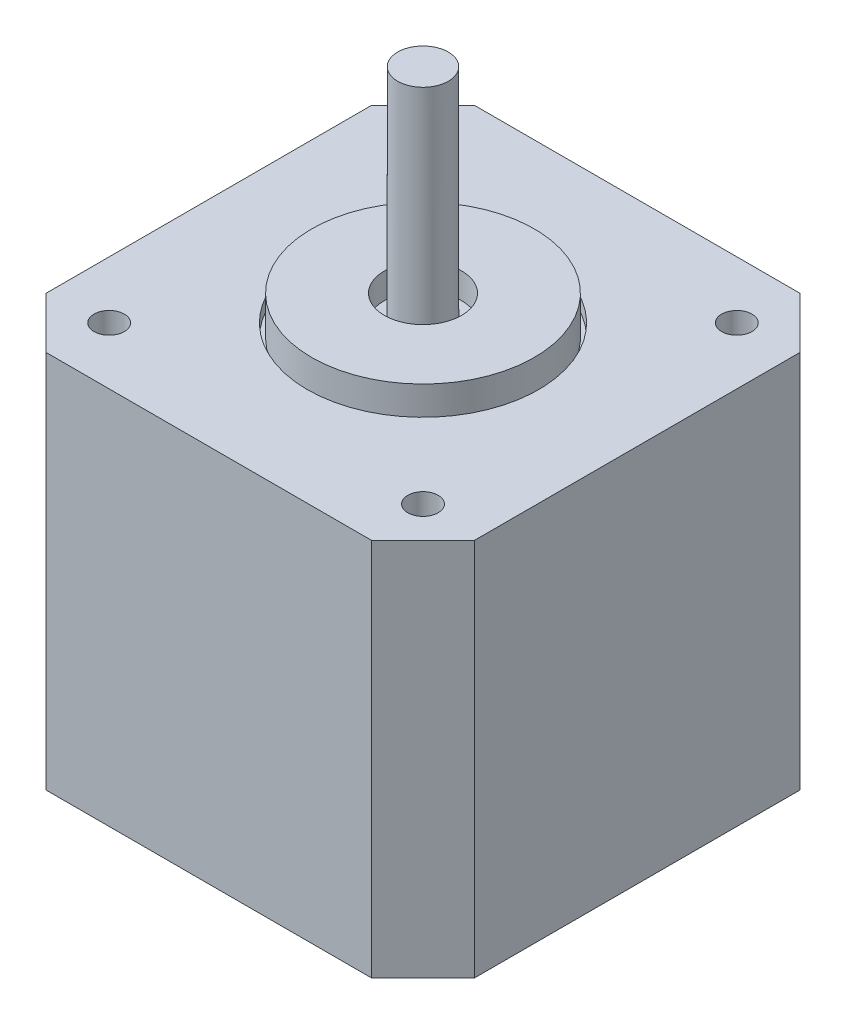
SolidWorks part; units mm, degrees
ref_plane "Front Plane" through (0, 0, 0) normal (0, 0, 1) x (1, 0, 0)
ref_plane "Top Plane" through (0, 0, 0) normal (0, 1, 0) x (1, 0, 0)
ref_plane "Right Plane" through (0, 0, 0) normal (1, 0, 0) x (0, 0, -1)
sketch "Sketch1" plane through (0, 0, 0) normal (0, 1, 0) x (1, 0, 0)
  line L1 (-21.15, -21.15) -> (21.15, -21.15)
  line L2 (-21.15, -21.15) -> (-21.15, 21.15)
  line L3 (-21.15, 21.15) -> (21.15, 21.15)
  line L4 (21.15, -21.15) -> (21.15, 21.15)
  line L5 (-21.15, -21.15) -> (21.15, 21.15) construction
  line L6 (-21.15, 21.15) -> (21.15, -21.15) construction
  point P0 (0, 0)
  dimension "D1" = 42.3
extrude "Boss-Extrude1" add sketch "Sketch1" along normal blind 37.4396
chamfer "Chamfer1" distance 5.08 angle 45 4 edges at (-21.15, 18.7198, 21.15) (-21.15, 18.7198, -21.15) (21.15, 18.7198, -21.15) (21.15, 18.7198, 21.15)
sketch "Sketch2" plane through (0, 37.4396, 0) normal (0, 1, 0) x (1, 0, 0)
  circle A0 centre (0, 0) radius 11
  circle A1 centre (0, 0) radius 11.43
  dimension "D1" = 22
  dimension "D2" = 22.86
extrude "Cut-Extrude1" cut sketch "Sketch2" against normal blind 1.27
sketch "Sketch3" plane through (0, 37.4396, 0) normal (0, 1, 0) x (1, 0, 0)
  circle A0 centre (0, 0) radius 11
  circle A1 centre (0, 0) radius 3.81
  dimension "D1" = 22
  dimension "D2" = 7.62
extrude "Boss-Extrude2" add sketch "Sketch3" along normal blind 2.54
sketch "Sketch4" plane through (0, 37.4396, 0) normal (0, 1, 0) x (1, 0, 0)
  circle A0 centre (0, 0) radius 2.5
  dimension "D1" = 5
extrude "Boss-Extrude3" add sketch "Sketch4" along normal blind 21.9202
sketch "Sketch5" plane through (0, 37.4396, 0) normal (0, 1, 0) x (1, 0, 0)
  line L0 (15.5, 15.5) -> (15.5, -15.5) construction
  line L1 (15.5, -15.5) -> (-15.5, -15.5) construction
  line L2 (-15.5, -15.5) -> (-15.5, 15.5) construction
  line L3 (-15.5, 15.5) -> (15.5, 15.5) construction
  line L4 (-15.5, -15.5) -> (15.5, 15.5) construction
  line L5 (-15.5, 15.5) -> (15.5, -15.5) construction
  circle A0 centre (15.5, 15.5) radius 1.5
  circle A1 centre (15.5, -15.5) radius 1.5
  circle A2 centre (-15.5, -15.5) radius 1.5
  circle A3 centre (-15.5, 15.5) radius 1.5
  point P8 (0, 0)
  dimension "D2" = 3
  dimension "D1" = 31
extrude "Cut-Extrude2" cut sketch "Sketch5" against normal up to next
